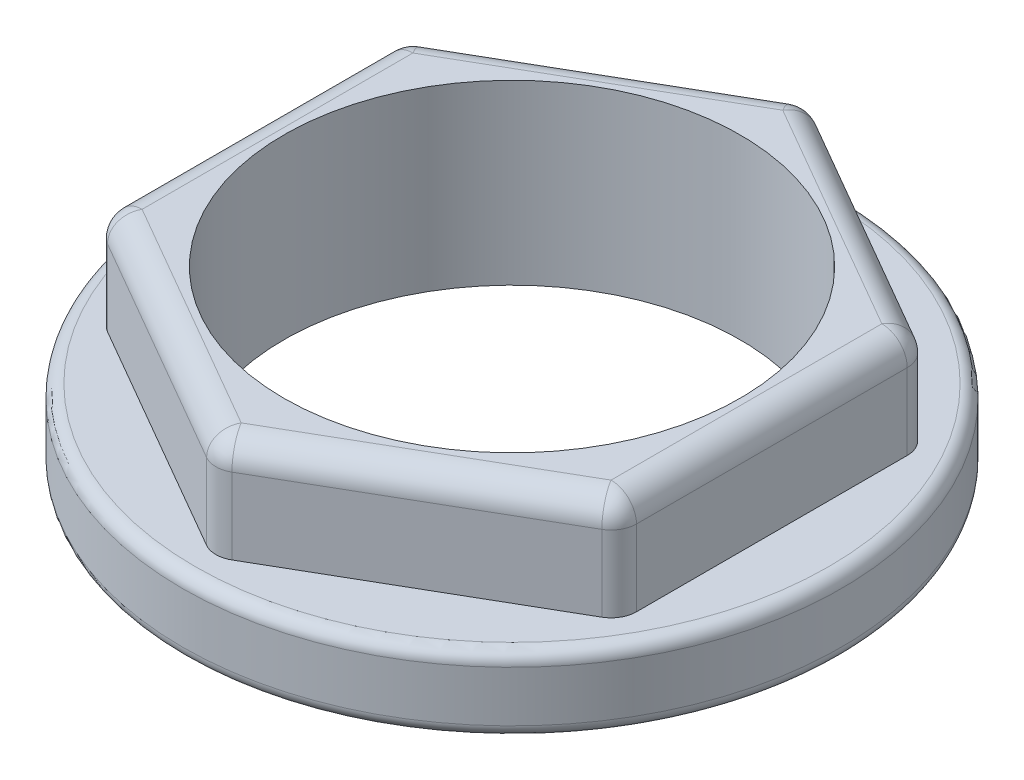
SolidWorks part; units mm, degrees
ref_plane "Plan de face" through (0, 0, 0) normal (0, 0, 1) x (1, 0, 0)
ref_plane "Plan de dessus" through (0, 0, 0) normal (0, 1, 0) x (1, 0, 0)
ref_plane "Plan de droite" through (0, 0, 0) normal (1, 0, 0) x (0, 0, -1)
sketch "Esquisse1" plane through (0, 0, 0) normal (0, 1, 0) x (1, 0, 0)
  circle A0 centre (0, 0) radius 13
  circle A1 centre (0, 0) radius 9
  dimension "D1" = 26
extrude "Boss.-Extru.1" add sketch "Esquisse1" along normal blind 3
sketch "Esquisse2" plane through (0, 3, 0) normal (0, 1, 0) x (1, 0, 0)
  line L1 (10.25, -5.9178) -> (10.25, 5.9178)
  line L2 (10.25, 5.9178) -> (0, 11.8357)
  line L3 (0, 11.8357) -> (-10.25, 5.9178)
  line L4 (-10.25, 5.9178) -> (-10.25, -5.9178)
  line L5 (-10.25, -5.9178) -> (0, -11.8357)
  line L6 (0, -11.8357) -> (10.25, -5.9178)
  circle A0 centre (0, 0) radius 10.25 construction
  circle A1 centre (0, 0) radius 9
  dimension "D2" = 18
  dimension "D1" = 20.5
extrude "Boss.-Extru.2" add sketch "Esquisse2" along normal blind 4
fillet "Congé2" radius 1 12 edges at (10.25, 5, -5.9178) (0, 5, -11.8357) (5.125, 7, -8.8768) (-5.125, 7, -8.8768) (-10.25, 5, -5.9178) (-10.25, 7, 0) (10.25, 7, 0) (5.125, 7, 8.8768) (-5.125, 7, 8.8768) (-10.25, 5, 5.9178) (10.25, 5, 5.9178) (0, 5, 11.8357)
fillet "Congé3" radius 0.5 2 edges at (0, 0, 13) (0, 3, 13)
